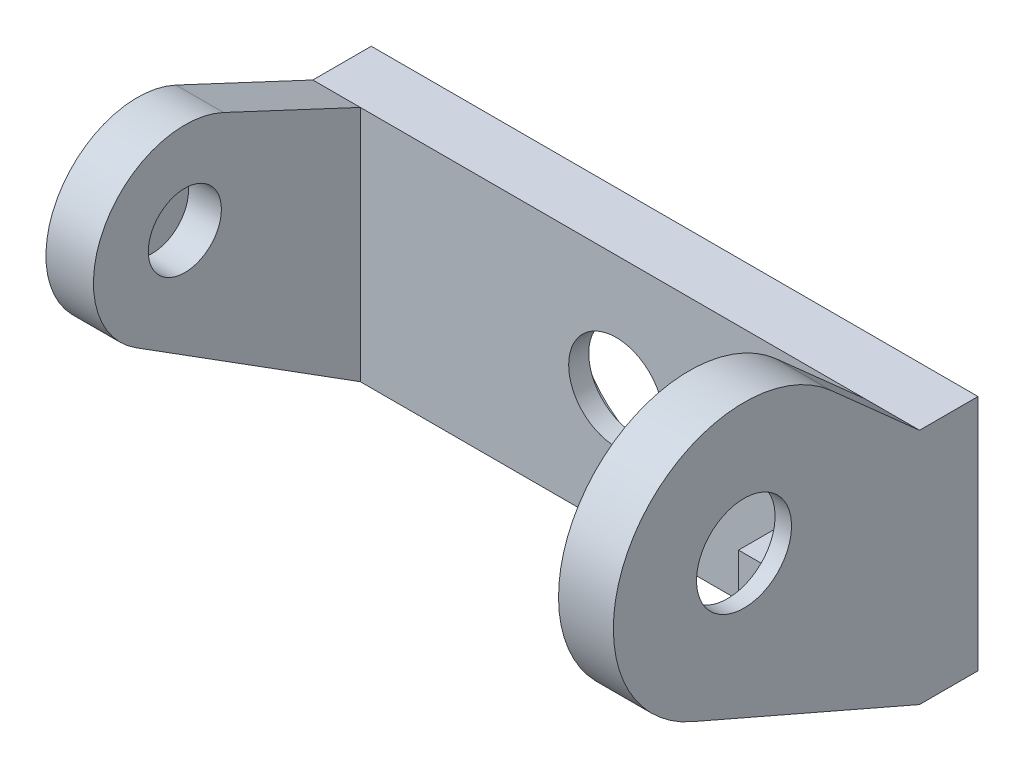
SolidWorks part; units mm, degrees
ref_plane "正面" through (0, 0, 0) normal (0, 0, 1) x (1, 0, 0)
ref_plane "平面" through (0, 0, 0) normal (0, 1, 0) x (1, 0, 0)
ref_plane "右側面" through (0, 0, 0) normal (1, 0, 0) x (0, 0, -1)
sketch "ｽｹｯﾁ1" plane through (0, 0, 0) normal (0, 0, 1) x (1, 0, 0)
  line L0 (0, 0) -> (13.6216, 0)
  line L1 (33.2, 0) -> (33.2, 13.0002)
  line L2 (33.2, 13.0002) -> (19.5784, 13.0002)
  line L3 (0, 13.0002) -> (0, 0)
  line L4 (16.6, 12.0053) -> (16.6, 0) construction
  line L5 (16.6, 6.5001) -> (33.2, 6.5001) construction
  line L6 (13.9218, 11.3099) -> (13.9218, 9.1783) construction
  line L7 (13.9218, 9.1783) -> (11.7902, 9.1783) construction
  line L8 (11.7902, 3.8219) -> (13.9218, 3.8219) construction
  line L9 (13.9218, 3.8219) -> (13.9218, 1.6903) construction
  line L10 (19.2782, 1.6903) -> (19.2782, 3.8219) construction
  line L11 (19.2782, 3.8219) -> (21.4098, 3.8219) construction
  line L12 (21.4098, 9.1783) -> (19.2782, 9.1783) construction
  line L13 (19.2782, 9.1783) -> (19.2782, 11.3099) construction
  line L14 (13.6216, 13.0002) -> (0, 13.0002)
  line L15 (19.5784, 0) -> (33.2, 0)
  line L16 (13.6216, 13.0002) -> (19.5784, 13.0002)
  line L17 (19.5784, 0) -> (13.6216, 0)
  line L18 (16.6, 12.0053) -> (16.6, 13.0002) construction
  arc A1 (11.7902, 9.1783) -> (11.7902, 3.8219) centre (16.6, 6.5001) ccw construction
  arc A2 (13.9218, 1.6903) -> (19.2782, 1.6903) centre (16.6, 6.5001) ccw construction
  arc A3 (21.4098, 3.8219) -> (21.4098, 9.1783) centre (16.6, 6.5001) ccw construction
  arc A4 (19.2782, 11.3099) -> (13.9218, 11.3099) centre (16.6, 6.5001) ccw construction
  dimension "D1" = 0.995
extrude "ﾎﾞｽ - 押し出し1" add sketch "ｽｹｯﾁ1" along normal blind 3.2
sketch "ｽｹｯﾁ2" plane through (0, 0, 0) normal (-1, 0, 0) x (0, 0, 1)
  line L3 (3.1997, 0) -> (15.472, 7.7447)
  line L4 (10.6849, 16.502) -> (3.1997, 13.0002)
  line L5 (3.1997, 13.0002) -> (3.1997, 0)
  arc A0 (15.472, 7.7447) -> (10.6849, 16.502) centre (12.8036, 11.9731) ccw
extrude "ﾎﾞｽ - 押し出し2" add sketch "ｽｹｯﾁ2" against normal blind 2.6
sketch "ｽｹｯﾁ3" plane through (33.2, 0, 0) normal (1, 0, 0) x (0, 0, -1)
  line L2 (-3.1997, 13.0002) -> (-8.0519, 17.3157)
  line L3 (-15.6549, 5.4162) -> (-3.1997, 0)
  line L5 (-3.1997, 13.0002) -> (-3.1997, 0)
  arc A0 (-8.0519, 17.3157) -> (-15.6549, 5.4162) centre (-12.8036, 11.9731) ccw
extrude "ﾎﾞｽ - 押し出し3" add sketch "ｽｹｯﾁ3" against normal blind 3
sketch "ｽｹｯﾁ4" plane through (0, 0, 0) normal (0, 0, -1) x (-1, 0, 0)
  line L0 (-21.833, 8.0233) -> (-20.3097, 6.5001)
  line L1 (-20.3097, 6.5001) -> (-21.833, 4.9769)
  line L2 (-18.1232, 1.2672) -> (-16.6, 2.7904)
  line L3 (-16.6, 2.7904) -> (-15.0768, 1.2672)
  line L4 (-11.367, 4.9769) -> (-12.8903, 6.5001)
  line L5 (-12.8903, 6.5001) -> (-11.367, 8.0233)
  line L6 (-21.8948, 8.0074) -> (-20.3875, 6.5001) construction
  line L7 (-20.3875, 6.5001) -> (-21.8948, 4.9929) construction
  line L8 (-18.1073, 1.2053) -> (-16.6, 2.7126) construction
  line L9 (-16.6, 2.7126) -> (-15.0927, 1.2053) construction
  line L10 (-11.3052, 4.9929) -> (-12.8125, 6.5001) construction
  line L11 (-12.8125, 6.5001) -> (-11.3052, 8.0074) construction
  line L12 (-15.0927, 11.7949) -> (-16.6, 10.2876) construction
  line L13 (-16.6, 10.2876) -> (-18.1073, 11.7949) construction
  line L14 (-15.0768, 11.7331) -> (-16.6, 10.2099)
  line L15 (-16.6, 10.2099) -> (-18.1232, 11.7331)
  arc A0 (-21.833, 4.9769) -> (-18.1232, 1.2672) centre (-16.6, 6.5001) ccw
  arc A1 (-21.8948, 4.9929) -> (-18.1073, 1.2053) centre (-16.6, 6.5001) ccw construction
  arc A2 (-15.0927, 1.2053) -> (-11.3052, 4.9929) centre (-16.6, 6.5001) ccw construction
  arc A3 (-11.3052, 8.0074) -> (-15.0927, 11.7949) centre (-16.6, 6.5001) ccw construction
  arc A4 (-18.1073, 11.7949) -> (-21.8948, 8.0074) centre (-16.6, 6.5001) ccw construction
  arc A5 (-15.0768, 1.2672) -> (-11.367, 4.9769) centre (-16.6, 6.5001) ccw
  arc A6 (-11.367, 8.0233) -> (-15.0768, 11.7331) centre (-16.6, 6.5001) ccw
  arc A7 (-18.1232, 11.7331) -> (-21.833, 8.0233) centre (-16.6, 6.5001) ccw
  dimension "D1" = 5.5051
extrude "ｶｯﾄ - 押し出し1" cut sketch "ｽｹｯﾁ4" against normal blind 2.1
sketch "ｽｹｯﾁ5" plane through (0, 0, 2.1) normal (0, 0, -1) x (-1, 0, 0)
  circle A0 centre (-16.6, 6.5001) radius 2.6
  dimension "D1" = 5.2
extrude "ｶｯﾄ - 押し出し2" cut sketch "ｽｹｯﾁ5" against normal up to vertex (1.1 mm away) up to point (30.2, 13.0002, 3.2)
sketch "ｽｹｯﾁ6" plane through (30.2, 0, 0) normal (-1, 0, 0) x (0, 0, 1)
  line L3 (15.5036, 7.1241) -> (15.5036, 9.2731)
  line L4 (15.5036, 9.2731) -> (17.6526, 9.2731)
  line L5 (17.6526, 14.6731) -> (15.5036, 14.6731)
  line L6 (15.5036, 14.6731) -> (15.5036, 16.8221)
  line L7 (10.1036, 16.8221) -> (10.1036, 14.6731)
  line L8 (10.1036, 14.6731) -> (7.9546, 14.6731)
  line L9 (7.9546, 9.2731) -> (10.1036, 9.2731)
  line L10 (10.1036, 9.2731) -> (10.1036, 7.1241)
  arc A1 (17.6526, 9.2731) -> (17.6526, 14.6731) centre (12.8036, 11.9731) ccw
  arc A2 (15.5036, 16.8221) -> (10.1036, 16.8221) centre (12.8036, 11.9731) ccw
  arc A3 (7.9546, 14.6731) -> (7.9546, 9.2731) centre (12.8036, 11.9731) ccw
  arc A4 (10.1036, 7.1241) -> (15.5036, 7.1241) centre (12.8036, 11.9731) ccw
extrude "ｶｯﾄ - 押し出し3" cut sketch "ｽｹｯﾁ6" against normal blind 2.1
sketch "ｽｹｯﾁ7" plane through (32.3, 0, 0) normal (-1, 0, 0) x (0, 0, 1)
  circle A0 centre (12.8036, 11.9731) radius 2.6
  dimension "D1" = 5.2
extrude "ｶｯﾄ - 押し出し4" cut sketch "ｽｹｯﾁ7" against normal up to vertex (0.9 mm away)
sketch "ｽｹｯﾁ8" plane through (2.6, 0, 0) normal (1, 0, 0) x (0, 0, -1)
  circle A0 centre (-12.8036, 11.9731) radius 2
  dimension "D1" = 4
extrude "ｶｯﾄ - 押し出し5" cut sketch "ｽｹｯﾁ8" against normal blind 1.8
